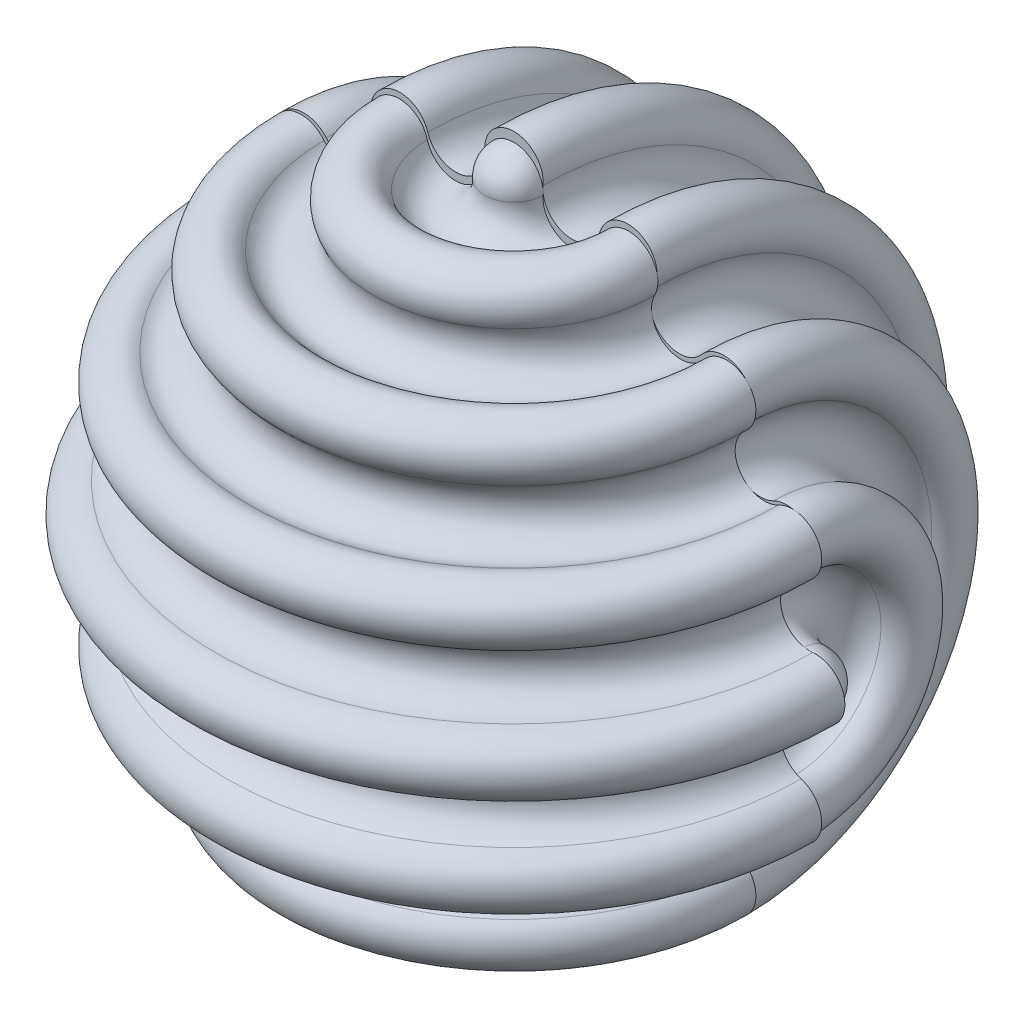
SolidWorks part; units mm, degrees
ref_plane "前视基准面" through (0, 0, 0) normal (0, 0, 1) x (1, 0, 0)
ref_plane "上视基准面" through (0, 0, 0) normal (0, 1, 0) x (1, 0, 0)
ref_plane "右视基准面" through (0, 0, 0) normal (1, 0, 0) x (0, 0, -1)
other "Configuration Table"
sketch "草图1" plane through (0, 0, 0) normal (0, 0, 1) x (1, 0, 0)
  line L1 (0, 83.0812) -> (0, 50) construction
  line L2 (0, -50) -> (0, -125.49) construction
  circle A18 centre (0, 0) radius 50 construction
  dimension "D1" = 100
sketch "草图4" plane through (0, 0, 0) normal (0, 0, 1) x (1, 0, 0)
  line L1 (0, -50) -> (0, -125.49) construction
  line L2 (0, 55) -> (0, -54.9492)
  arc A1 (4.9883, 49.6588) -> (14.7974, 47.9907) centre (9.9767, 49.3177) ccw
  arc A11 (4.9883, 49.6588) -> (0, 55) centre (0, 50) ccw
  arc A12 (24.0783, 44.4039) -> (14.7974, 47.9907) centre (19.6181, 46.6637) ccw
  arc A13 (24.0783, 44.4039) -> (32.4598, 39.042) centre (28.5385, 42.1441) ccw
  arc A14 (39.6067, 32.1194) -> (32.4598, 39.042) centre (36.3811, 35.9398) ccw
  arc A15 (39.6067, 32.1194) -> (45.2331, 23.9131) centre (42.8323, 28.299) ccw
  arc A16 (49.1139, 14.7512) -> (45.2331, 23.9131) centre (47.6339, 19.5272) ccw
  arc A17 (49.1139, 14.7512) -> (51.0939, 5.0003) centre (50.5939, 9.9753) ccw
  arc A18 (51.0939, -4.9495) -> (51.0939, 5.0003) centre (51.5939, 0.0254) ccw
  arc A19 (51.0939, -4.9495) -> (49.1139, -14.7004) centre (50.5939, -9.9245) ccw
  arc A20 (45.2331, -23.8622) -> (49.1139, -14.7004) centre (47.6339, -19.4763) ccw
  arc A21 (45.2331, -23.8622) -> (39.6067, -32.0686) centre (42.8323, -28.2482) ccw
  arc A22 (32.4598, -38.9912) -> (39.6067, -32.0686) centre (36.3811, -35.889) ccw
  arc A23 (32.4598, -38.9912) -> (24.0783, -44.3531) centre (28.5385, -42.0933) ccw
  arc A24 (14.7974, -47.9399) -> (24.0783, -44.3531) centre (19.6181, -46.6128) ccw
  arc A25 (14.7974, -47.9399) -> (4.9883, -49.608) centre (9.9767, -49.2669) ccw
  arc A26 (0, -54.9492) -> (4.9883, -49.608) centre (0, -49.9492) ccw
  dimension "D1" = 10
  dimension "D3" = 17
revolve "旋转4" add sketch "草图4" angle 180 about L2
mirror "镜向6" of bodies 122
move or copy body "实体-移动/复制6" bodies to move or copy 123 copy no rotation origin (0, 0.0254, 0) rotation axis (0, 0, 1) rotation angle 90
combine bodies "组合2" operation type add bodies to combine 124 122
